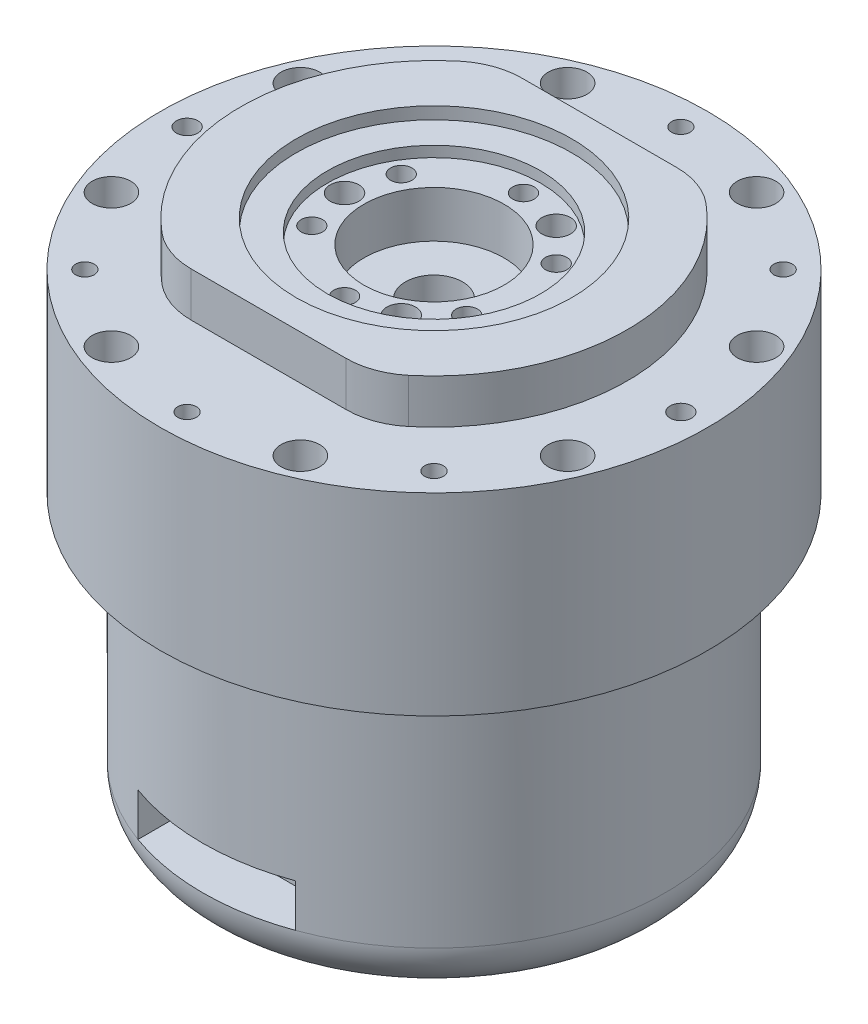
SolidWorks part; units mm, degrees
ref_plane "前视基准面" through (0, 0, 0) normal (0, 0, 1) x (1, 0, 0)
ref_plane "上视基准面" through (0, 0, 0) normal (0, 1, 0) x (1, 0, 0)
ref_plane "右视基准面" through (0, 0, 0) normal (1, 0, 0) x (0, 0, -1)
other "Configuration Table"
sketch "草图1" plane through (0, 0, 0) normal (0, 1, 0) x (1, 0, 0)
  line L0 (-38.25, 0) -> (38.25, 0) construction
  line L1 (-13.9782, 23.1) -> (13.9782, 23.1)
  line L2 (-13.9782, -23.1) -> (13.9782, -23.1)
  line L3 (0, 12.5) -> (0, 0) construction
  line L4 (0, 0) -> (6.25, 10.8253) construction
  line L5 (13.2026, 31.8738) -> (0, 0) construction
  line L6 (0, 0) -> (0, 34.5) construction
  circle A0 centre (0, 0) radius 12.5 construction
  circle A1 centre (0, 0) radius 38.25
  circle A2 centre (0, 0) radius 34.5 construction
  circle A3 centre (0, 0) radius 27
  circle A4 centre (0, 34.5) radius 1.3
  circle A5 centre (24.3952, 24.3952) radius 1.3
  circle A6 centre (34.5, 0) radius 1.3
  circle A7 centre (24.3952, -24.3952) radius 1.3
  circle A8 centre (0, -34.5) radius 1.3
  circle A9 centre (-24.3952, -24.3952) radius 1.3
  circle A10 centre (-34.5, 0) radius 1.3
  circle A11 centre (-24.3952, 24.3952) radius 1.3
  circle A12 centre (0, 12.5) radius 1.5
  circle A13 centre (10.8253, 6.25) radius 1.5
  circle A14 centre (10.8253, -6.25) radius 1.5
  circle A15 centre (0, -12.5) radius 1.5
  circle A16 centre (-10.8253, -6.25) radius 1.5
  circle A17 centre (-10.8253, 6.25) radius 1.5
  circle A18 centre (6.25, 10.8253) radius 2
  circle A19 centre (6.25, -10.8253) radius 2
  circle A20 centre (-12.5, 0) radius 2
  circle A21 centre (0, 0) radius 19.25
  circle A22 centre (0, 0) radius 14.9 construction
  circle A23 centre (0, 0) radius 9.8 construction
  circle A24 centre (13.2026, 31.8738) radius 2.7
  circle A25 centre (31.8738, 13.2026) radius 2.7
  circle A26 centre (31.8738, -13.2026) radius 2.7
  circle A27 centre (13.2026, -31.8738) radius 2.7
  circle A28 centre (-13.2026, -31.8738) radius 2.7
  circle A29 centre (-31.8738, -13.2026) radius 2.7
  circle A30 centre (-31.8738, 13.2026) radius 2.7
  circle A31 centre (-13.2026, 31.8738) radius 2.7
  point P30 (0, 0)
  point P43 (0, 0)
  point P50 (0, 0)
  point P70 (0, 0)
  dimension "D1" = 25
  dimension "D2" = 76.5
  dimension "D3" = 69
  dimension "D4" = 54
  dimension "D6" = 2.6
  dimension "D8" = 3
  dimension "D11" = 4
  dimension "D13" = 38.5
  dimension "D14" = 29.8
  dimension "D15" = 19.6
  dimension "D16" = 5.4
  dimension "D5" = 46.2
  dimension "D10" = 30
  dimension "D17" = 22.5
  dimension "D7" = 8
  dimension "D9" = 6
  dimension "D12" = 3
  dimension "D18" = 8
sketch "草图2" plane through (0, 0, 0) normal (0, 1, 0) x (1, 0, 0)
  circle A3 centre (0, 34.5) radius 1.3
  circle A4 centre (0, 34.5) radius 1.3
  circle A7 centre (0, 0) radius 38.25
  circle A8 centre (0, 0) radius 38.25
  circle A9 centre (-24.3952, 24.3952) radius 1.3
  circle A10 centre (-24.3952, 24.3952) radius 1.3
  circle A11 centre (-34.5, 0) radius 1.3
  circle A12 centre (-34.5, 0) radius 1.3
  circle A13 centre (-24.3952, -24.3952) radius 1.3
  circle A14 centre (-24.3952, -24.3952) radius 1.3
  circle A15 centre (0, -34.5) radius 1.3
  circle A16 centre (0, -34.5) radius 1.3
  circle A17 centre (24.3952, -24.3952) radius 1.3
  circle A18 centre (24.3952, -24.3952) radius 1.3
  circle A19 centre (34.5, 0) radius 1.3
  circle A20 centre (34.5, 0) radius 1.3
  circle A21 centre (24.3952, 24.3952) radius 1.3
  circle A22 centre (24.3952, 24.3952) radius 1.3
  dimension "D2" = 0
  dimension "D4" = 0
  dimension "D5" = 0
  dimension "D6" = 0
  dimension "D7" = 0
  dimension "D8" = 0
  dimension "D9" = 0
  dimension "D10" = 0
  dimension "D11" = 0
extrude "凸台-拉伸1" add sketch "草图2" along normal blind 27
cosmetic thread "装饰螺纹线2" parameters "D2"=3
cosmetic thread "装饰螺纹线3" parameters "D2"=3
cosmetic thread "装饰螺纹线4" parameters "D2"=3
cosmetic thread "装饰螺纹线5" parameters "D2"=3
cosmetic thread "装饰螺纹线6" parameters "D2"=3
cosmetic thread "装饰螺纹线7" parameters "D2"=3
sketch "草图3" plane through (0, 27, 0) normal (0, 1, 0) x (1, 0, 0)
  line L0 (-13.9782, 23.1) -> (13.9782, 23.1) construction
  line L1 (-13.9782, 23.1) -> (13.9782, 23.1)
  line L2 (-13.9782, -23.1) -> (13.9782, -23.1) construction
  line L3 (-13.9782, -23.1) -> (13.9782, -23.1)
  circle A0 centre (0, 0) radius 27 construction
  arc A1 (-13.9782, 23.1) -> (-13.9782, -23.1) centre (0, 0) ccw
  arc A2 (13.9782, -23.1) -> (13.9782, 23.1) centre (0, 0) ccw
extrude "凸台-拉伸2" add sketch "草图3" along normal blind 6.2
sketch "草图4" plane through (0, 33.2, 0) normal (0, 1, 0) x (1, 0, 0)
  circle A0 centre (0, 0) radius 19.25 construction
  circle A1 centre (0, 0) radius 19.25
extrude "切除-拉伸1" cut sketch "草图4" against normal blind 1.7
sketch "草图5" plane through (0, 33.2, 0) normal (0, 1, 0) x (1, 0, 0)
  circle A0 centre (0, 0) radius 14.9 construction
  circle A1 centre (0, 0) radius 14.9
extrude "切除-拉伸2" cut sketch "草图5" against normal blind 3.2
sketch "草图6" plane through (0, 30, 0) normal (0, 1, 0) x (1, 0, 0)
  circle A0 centre (0, -12.5) radius 1.5 construction
  circle A1 centre (10.8253, -6.25) radius 1.5 construction
  circle A2 centre (10.8253, 6.25) radius 1.5 construction
  circle A3 centre (-10.8253, -6.25) radius 1.5 construction
  circle A4 centre (-10.8253, 6.25) radius 1.5 construction
  circle A5 centre (0, 12.5) radius 1.5 construction
  circle A6 centre (0, -12.5) radius 1.5
  circle A7 centre (10.8253, -6.25) radius 1.5
  circle A8 centre (10.8253, 6.25) radius 1.5
  circle A9 centre (-10.8253, -6.25) radius 1.5
  circle A10 centre (-10.8253, 6.25) radius 1.5
  circle A11 centre (0, 12.5) radius 1.5
extrude "切除-拉伸3" cut sketch "草图6" against normal blind 8
cosmetic thread "装饰螺纹线8" parameters "D2"=3
cosmetic thread "装饰螺纹线9" parameters "D2"=3
cosmetic thread "装饰螺纹线10" parameters "D2"=3
cosmetic thread "装饰螺纹线11" parameters "D2"=3
cosmetic thread "装饰螺纹线12" parameters "D2"=3
cosmetic thread "装饰螺纹线13" parameters "D2"=3
sketch "草图7" plane through (0, 30, 0) normal (0, 1, 0) x (1, 0, 0)
  circle A0 centre (-12.5, 0) radius 2 construction
  circle A1 centre (6.25, -10.8253) radius 2 construction
  circle A2 centre (6.25, 10.8253) radius 2 construction
  circle A3 centre (-12.5, 0) radius 2
  circle A4 centre (6.25, -10.8253) radius 2
  circle A5 centre (6.25, 10.8253) radius 2
extrude "切除-拉伸4" cut sketch "草图7" against normal blind 4.5
sketch "草图8" plane through (0, 0, 0) normal (0, 1, 0) x (1, 0, 0)
  circle A0 centre (0, 0) radius 32.3
  dimension "D1" = 64.6
extrude "凸台-拉伸3" add sketch "草图8" along direction (0, 1, 0) on the side against the normal blind 39.3
fillet "圆角1" radius 7 1 edges at (0, -39.3, 32.3)
fillet "圆角2" radius 10 4 edges at (-13.9782, 30.1, -23.1) (13.9782, 30.1, 23.1) (-13.9782, 30.1, 23.1) (13.9782, 30.1, -23.1)
ref_plane "基准面1" through (0, 0, 40) normal (0, 0, 1) x (1, 0, 0)
ref_plane "基准面2" through (0, 0, -40) normal (0, 0, 1) x (1, 0, 0)
sketch "草图9" plane through (0, 0, 40) normal (0, 0, 1) x (1, 0, 0)
  line L0 (32.3, -32.3) -> (-32.3, -32.3) construction
  line L1 (-11, -26.3) -> (11, -26.3)
  line L2 (-11, -26.3) -> (-11, -32.3)
  line L3 (-11, -32.3) -> (11, -32.3)
  line L4 (11, -26.3) -> (11, -32.3)
  line L5 (-11, -26.3) -> (11, -32.3) construction
  line L6 (-11, -32.3) -> (11, -26.3) construction
  point P0 (0, -29.3)
  dimension "D1" = 22
  dimension "D2" = 6
extrude "切除-拉伸5" cut sketch "草图9" against normal blind 15
sketch "草图10" plane through (0, 0, -40) normal (0, 0, 1) x (1, 0, 0)
  line L0 (32.3, -32.3) -> (-32.3, -32.3) construction
  line L1 (11, -37.3) -> (-11, -37.3)
  line L2 (11, -37.3) -> (11, -24.3)
  line L3 (11, -24.3) -> (-11, -24.3)
  line L4 (-11, -37.3) -> (-11, -24.3)
  line L5 (11, -37.3) -> (-11, -24.3) construction
  line L6 (11, -24.3) -> (-11, -37.3) construction
  point P0 (0, -30.8)
  dimension "D1" = 22
  dimension "D2" = 8
  dimension "D3" = 5
extrude "切除-拉伸6" cut sketch "草图10" along normal blind 15
sketch "草图12" plane through (0, 30, 0) normal (0, 1, 0) x (1, 0, 0)
  circle A0 centre (0, 0) radius 9.8 construction
  circle A1 centre (0, 0) radius 9.8
extrude "切除-拉伸7" cut sketch "草图12" against normal blind 6.5
sketch "草图13" plane through (0, 23.5, 0) normal (0, 1, 0) x (1, 0, 0)
  circle A0 centre (0, 0) radius 4
  dimension "D1" = 8
extrude "切除-拉伸8" cut sketch "草图13" against normal blind 6
sketch "草图14" plane through (0, 27, 0) normal (0, 1, 0) x (1, 0, 0)
  circle A0 centre (31.8738, 13.2026) radius 2.7 construction
  circle A1 centre (31.8738, -13.2026) radius 2.7 construction
  circle A2 centre (13.2026, -31.8738) radius 2.7 construction
  circle A3 centre (-13.2026, -31.8738) radius 2.7 construction
  circle A4 centre (-31.8738, -13.2026) radius 2.7 construction
  circle A5 centre (-31.8738, 13.2026) radius 2.7 construction
  circle A6 centre (-13.2026, 31.8738) radius 2.7 construction
  circle A7 centre (13.2026, 31.8738) radius 2.7 construction
  circle A8 centre (31.8738, 13.2026) radius 2.7
  circle A9 centre (31.8738, -13.2026) radius 2.7
  circle A10 centre (13.2026, -31.8738) radius 2.7
  circle A11 centre (-13.2026, -31.8738) radius 2.7
  circle A12 centre (-31.8738, -13.2026) radius 2.7
  circle A13 centre (-31.8738, 13.2026) radius 2.7
  circle A14 centre (-13.2026, 31.8738) radius 2.7
  circle A15 centre (13.2026, 31.8738) radius 2.7
extrude "切除-拉伸9" cut sketch "草图14" against normal blind 7
sketch "草图15" plane through (0, 0, 0) normal (0, -1, 0) x (1, 0, 0)
  circle A0 centre (13.2026, 31.8738) radius 1.2
  circle A1 centre (-13.2026, 31.8738) radius 1.2
  circle A2 centre (-31.8738, 13.2026) radius 1.2
  circle A3 centre (-31.8738, -13.2026) radius 1.2
  circle A4 centre (-13.2026, -31.8738) radius 1.2
  circle A5 centre (13.2026, -31.8738) radius 1.2
  circle A6 centre (31.8738, -13.2026) radius 1.2
  circle A7 centre (31.8738, 13.2026) radius 1.2
  dimension "D1" = 2.4
extrude "切除-拉伸10" cut sketch "草图15" against normal blind 4
cosmetic thread "装饰螺纹线15" parameters "D2"=2.5
cosmetic thread "装饰螺纹线16" parameters "D2"=2.5
cosmetic thread "装饰螺纹线17" parameters "D2"=2.5
cosmetic thread "装饰螺纹线18" parameters "D2"=2.5
cosmetic thread "装饰螺纹线19" parameters "D2"=2.5
cosmetic thread "装饰螺纹线20" parameters "D2"=2.5
cosmetic thread "装饰螺纹线21" parameters "D2"=2.5
cosmetic thread "装饰螺纹线23" parameters "D2"=2.5
sketch "草图16" plane through (0, 0, 0) normal (0, -1, 0) x (1, 0, 0)
  circle A1 centre (-24.3952, -24.3952) radius 1.3 construction
  circle A2 centre (0, -34.5) radius 1.3 construction
  circle A3 centre (24.3952, -24.3952) radius 1.3 construction
  circle A5 centre (24.3952, 24.3952) radius 1.3 construction
  circle A6 centre (0, 34.5) radius 1.3 construction
  circle A7 centre (-24.3952, 24.3952) radius 1.3 construction
  circle A9 centre (-24.3952, -24.3952) radius 1.3
  circle A10 centre (0, -34.5) radius 1.3
  circle A11 centre (24.3952, -24.3952) radius 1.3
  circle A13 centre (24.3952, 24.3952) radius 1.3
  circle A14 centre (0, 34.5) radius 1.3
  circle A15 centre (-24.3952, 24.3952) radius 1.3
  circle A16 centre (0, 34.5) radius 1.2
  circle A17 centre (0, -34.5) radius 1.2
  dimension "D1" = 2.4
extrude "凸台-拉伸4" add sketch "草图16" against normal blind 12
cosmetic thread "装饰螺纹线14" parameters "D2"=2.5
cosmetic thread "装饰螺纹线22" parameters "D2"=2.5
ref_plane "基准面3" through (0, 8, 0) normal (0, -1, 0) x (-1, 0, 0)
sketch "草图18" plane through (0, 8, 0) normal (0, -1, 0) x (-1, 0, 0)
  circle A0 centre (34.5, 0) radius 1.3 construction
  circle A1 centre (-34.5, 0) radius 1.3 construction
  circle A2 centre (34.5, 0) radius 1.3
  circle A3 centre (-34.5, 0) radius 1.3
extrude "凸台-拉伸5" add sketch "草图18" against normal blind 9
sketch "草图19" plane through (0, 27, 0) normal (0, 1, 0) x (1, 0, 0)
  circle A0 centre (-34.5, 0) radius 1.5
  circle A1 centre (34.5, 0) radius 1.5
  dimension "D1" = 3
extrude "切除-拉伸11" cut sketch "草图19" against normal up to surface (10 mm away) up to face at (-34.5, 17, -1.3)
